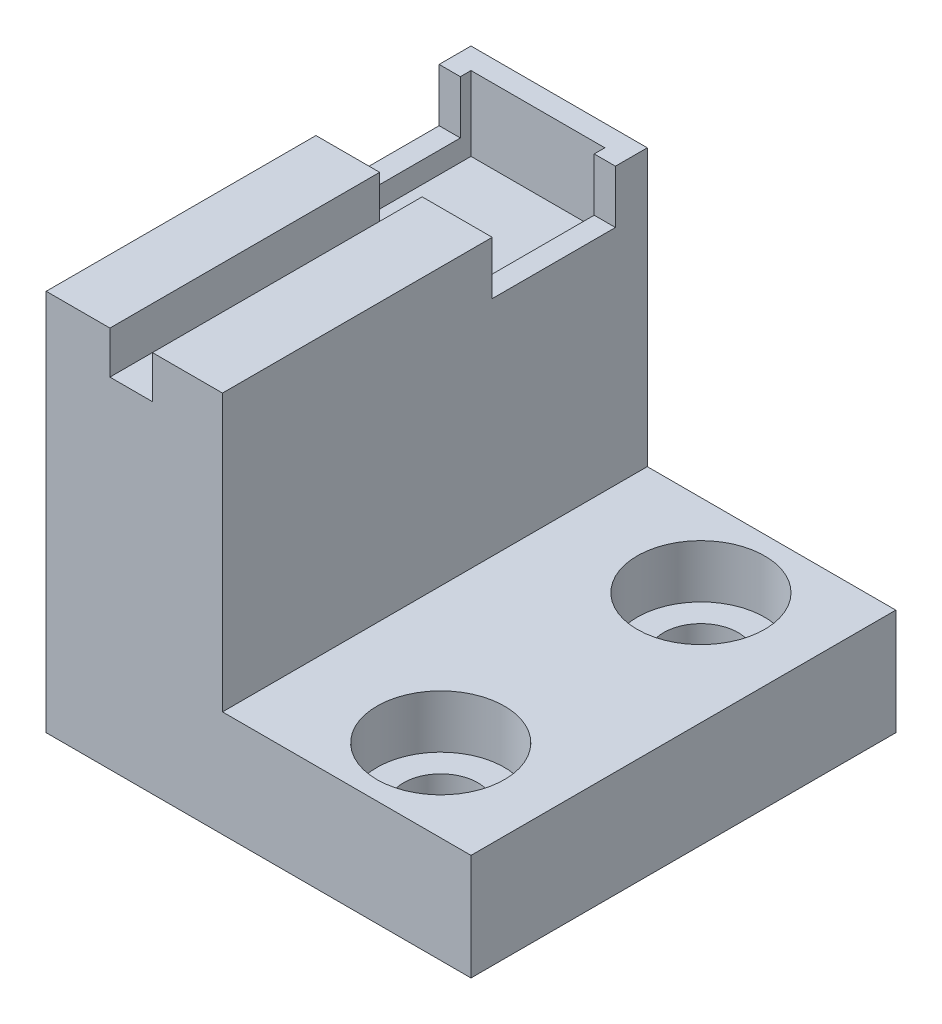
SolidWorks part; units mm, degrees
ref_plane "前视基准面" through (0, 0, 0) normal (0, 0, 1) x (1, 0, 0)
ref_plane "上视基准面" through (0, 0, 0) normal (0, 1, 0) x (1, 0, 0)
ref_plane "右视基准面" through (0, 0, 0) normal (1, 0, 0) x (0, 0, -1)
other "Configuration Table"
sketch "草图1" plane through (0, 0, 0) normal (0, 1, 0) x (1, 0, 0)
  line L1 (-20, 20) -> (20, 20)
  line L2 (-20, 20) -> (-20, -20)
  line L3 (-20, -20) -> (20, -20)
  line L4 (20, 20) -> (20, -20)
  line L5 (-20, 20) -> (20, -20) construction
  line L6 (-20, -20) -> (20, 20) construction
  point P0 (0, 0)
  dimension "D1" = 40
  dimension "D2" = 40
extrude "凸台-拉伸1" add sketch "草图1" along normal blind 36
sketch "草图2" plane through (0, 36, 0) normal (0, 1, 0) x (1, 0, 0)
  line L0 (20, 20) -> (-20, 20) construction
  line L1 (-18, 18) -> (-5.4, 18)
  line L2 (-18, 18) -> (-18, 5.4)
  line L3 (-18, 5.4) -> (-5.4, 5.4)
  line L4 (-5.4, 18) -> (-5.4, 5.4)
  line L5 (-18, 18) -> (-5.4, 5.4) construction
  line L6 (-18, 5.4) -> (-5.4, 18) construction
  line L7 (-20, 20) -> (-20, -20) construction
  point P0 (-11.7, 11.7)
  dimension "D1" = 12.6
  dimension "D2" = 12.6
  dimension "D3" = 2
  dimension "D4" = 2
extrude "切除-拉伸1" cut sketch "草图2" against normal blind 7
sketch "草图3" plane through (0, 36, 0) normal (0, 1, 0) x (1, 0, 0)
  line L0 (-20, 20) -> (-20, -20) construction
  line L1 (-20, 17) -> (-18, 17)
  line L2 (-20, 17) -> (-20, 5.4)
  line L3 (-20, 5.4) -> (-18, 5.4)
  line L4 (-18, 17) -> (-18, 5.4)
  line L5 (-18, 18) -> (-18, 5.4) construction
  line L6 (20, 20) -> (-20, 20) construction
  line L7 (-18, 5.4) -> (-5.4, 5.4) construction
  line L9 (-5.4, 5.4) -> (-3.4, 5.4)
  line L10 (-5.4, 5.4) -> (-5.4, 17)
  line L11 (-5.4, 17) -> (-3.4, 17)
  line L12 (-3.4, 5.4) -> (-3.4, 17)
  dimension "D1" = 3
  dimension "D2" = 0
  dimension "D3" = 2
extrude "切除-拉伸2" cut sketch "草图3" against normal blind 5
sketch "草图4" plane through (0, 36, 0) normal (0, 1, 0) x (1, 0, 0)
  line L0 (-20, 5.4) -> (-3.4, 5.4) construction
  line L1 (-14, 5.4) -> (-10, 5.4)
  line L2 (-14, 5.4) -> (-14, -20)
  line L3 (-14, -20) -> (-10, -20)
  line L4 (-10, 5.4) -> (-10, -20)
  line L5 (-20, -20) -> (20, -20) construction
  line L6 (-20, 5.4) -> (-20, -20) construction
  dimension "D1" = 4
  dimension "D2" = 6
extrude "切除-拉伸3" cut sketch "草图4" against normal blind 4
sketch "草图5" plane through (0, 36, 0) normal (0, 1, 0) x (1, 0, 0)
  line L1 (20, 20) -> (-20, 20) construction
  line L2 (-3.4, 20) -> (20, 20)
  line L3 (-3.4, 20) -> (-3.4, -20)
  line L4 (-3.4, -20) -> (20, -20)
  line L5 (20, 20) -> (20, -20)
  line L6 (-5.4, 5.4) -> (-5.4, 18) construction
  dimension "D2" = 2
extrude "切除-拉伸6" cut sketch "草图5" against normal blind 26
sketch "草图6" plane through (0, 10, 0) normal (0, 1, 0) x (1, 0, 0)
  line L0 (-20, 17) -> (-20, 5.4) construction
  line L1 (20, 20) -> (-3.4, 20) construction
  line L2 (-3.4, -20) -> (20, -20) construction
  circle A0 centre (9.4, 12.25) radius 6
  circle A1 centre (9.4, -12.25) radius 6
  dimension "D1" = 12
  dimension "D4" = 12
  dimension "D2" = 29.4
  dimension "D3" = 7.75
  dimension "D5" = 7.75
extrude "切除-拉伸7" cut sketch "草图6" against normal blind 5
sketch "草图7" plane through (0, 10, 0) normal (0, 1, 0) x (1, 0, 0)
  circle A0 centre (9.4, 12.25) radius 3.5
  circle A1 centre (9.4, -12.25) radius 3.5
  dimension "D1" = 7
  dimension "D2" = 7
extrude "切除-拉伸8" cut sketch "草图7" against normal through all
